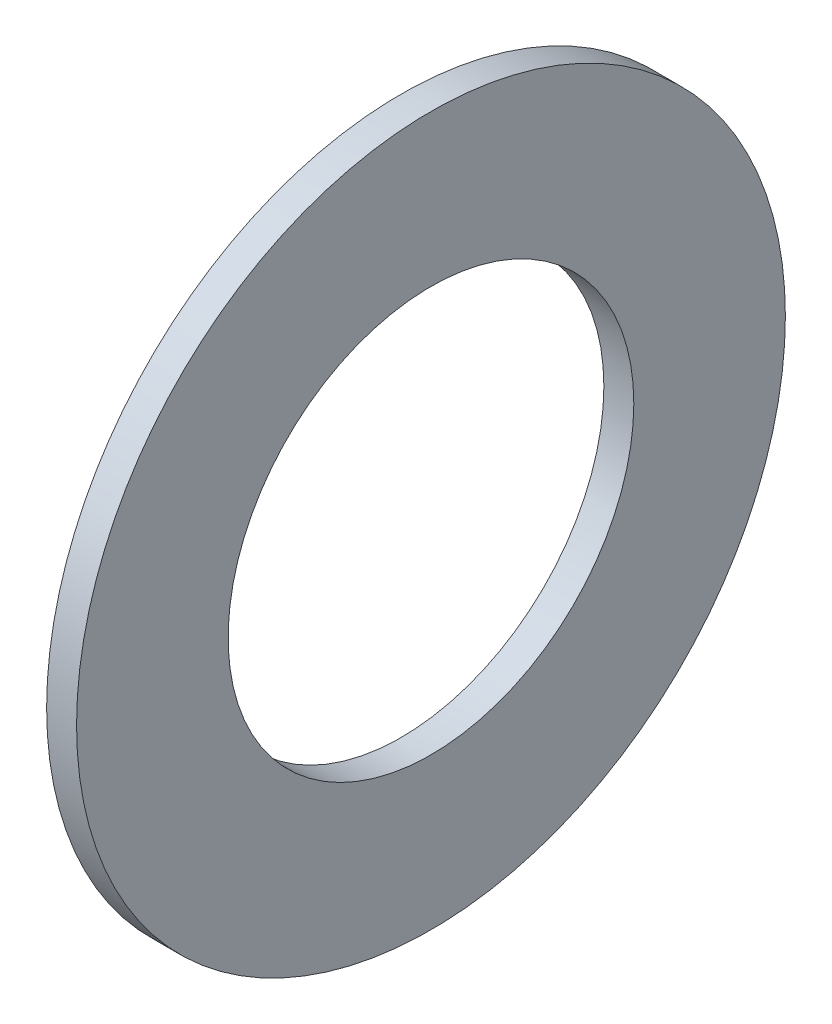
SolidWorks part; units mm, degrees
ref_plane "Ebene vorne" through (0, 0, 0) normal (0, 0, 1) x (1, 0, 0)
ref_plane "Ebene oben" through (0, 0, 0) normal (0, 1, 0) x (1, 0, 0)
ref_plane "Ebene rechts" through (0, 0, 0) normal (1, 0, 0) x (0, 0, -1)
sketch "Sketch1" plane through (0, 0, 0) normal (1, 0, 0) x (0, 0, -1)
  circle A0 centre (0, 0) radius 27.1
  circle A1 centre (0, 0) radius 47.35
  dimension "D1" = 54.2
  dimension "D2" = 94.7
extrude "Boss-Extrude1" add sketch "Sketch1" along normal blind 4
